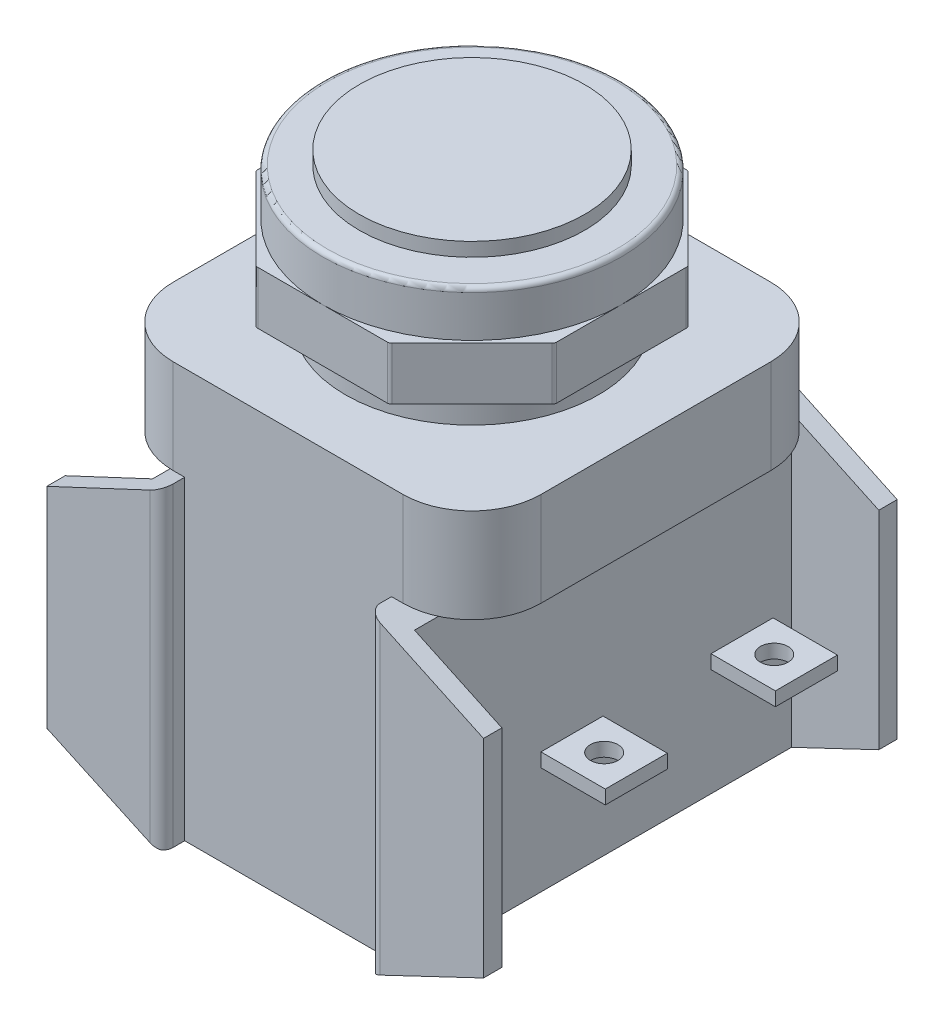
SolidWorks part; units mm, degrees
ref_plane "Front Plane" through (0, 0, 0) normal (0, 0, 1) x (1, 0, 0)
ref_plane "Top Plane" through (0, 0, 0) normal (0, 1, 0) x (1, 0, 0)
ref_plane "Right Plane" through (0, 0, 0) normal (1, 0, 0) x (0, 0, -1)
sketch "Sketch1" plane through (0, 0, 0) normal (0, 1, 0) x (1, 0, 0)
  circle A0 centre (0, 0) radius 12.446
  dimension "D1" = 24.892
extrude "Boss-Extrude1" add sketch "Sketch1" against normal blind 1.524
sketch "Sketch2" plane through (0, -1.524, 0) normal (0, -1, 0) x (1, 0, 0)
  circle A0 centre (0, 0) radius 16.51
  dimension "D1" = 33.02
extrude "Boss-Extrude2" add sketch "Sketch2" along normal blind 5.08
sketch "Sketch3" plane through (0, -6.604, 0) normal (0, -1, 0) x (1, 0, 0)
  line L0 (0, 0) -> (16.51, 0) construction
  line L1 (0, 0) -> (0, -16.51) construction
  line L2 (16.51, 7.366) -> (16.51, -7.366)
  line L3 (-7.366, -16.51) -> (7.366, -16.51)
  line L4 (16.51, -7.366) -> (7.366, -16.51)
  line L5 (-7.366, 16.51) -> (7.366, 16.51)
  line L6 (16.51, 7.366) -> (7.366, 16.51)
  line L7 (-16.51, -7.366) -> (-7.366, -16.51)
  line L8 (-16.51, 7.366) -> (-16.51, -7.366)
  line L9 (-16.51, 7.366) -> (-7.366, 16.51)
  circle A0 centre (0, 0) radius 16.51 construction
  point P16 (0, 16.51)
  dimension "D1" = 7.366
  dimension "D2" = 7.366
extrude "Boss-Extrude3" add sketch "Sketch3" along normal blind 5.842
fillet "Fillet1" radius 0.508 1 edges at (0, -1.524, -16.51)
fillet "Fillet2" radius 0.508 8 edges at (-7.366, -9.525, -16.51) (7.366, -9.525, -16.51) (16.51, -9.525, -7.366) (16.51, -9.525, 7.366) (7.366, -9.525, 16.51) (-7.366, -9.525, 16.51) (-16.51, -9.525, 7.366) (-16.51, -9.525, -7.366)
sketch "Sketch4" plane through (0, -12.446, 0) normal (0, -1, 0) x (1, 0, 0)
  circle A0 centre (0, 0) radius 13.97
  dimension "D1" = 27.94
extrude "Boss-Extrude4" add sketch "Sketch4" along normal blind 4.064
sketch "Sketch5" plane through (0, -16.51, 0) normal (0, -1, 0) x (1, 0, 0)
  line L0 (0, 0) -> (20.32, 0) construction
  line L1 (20.32, 0) -> (20.32, 20.32) construction
  line L2 (12.7, 20.32) -> (-12.7, 20.32)
  line L3 (-20.32, 12.7) -> (-20.32, -12.7)
  line L4 (-12.7, -20.32) -> (12.7, -20.32)
  line L5 (20.32, -12.7) -> (20.32, 12.7)
  arc A0 (-20.32, 12.7) -> (-12.7, 20.32) centre (-12.7, 12.7) cw
  arc A1 (12.7, 20.32) -> (20.32, 12.7) centre (12.7, 12.7) cw
  arc A2 (-20.32, -12.7) -> (-12.7, -20.32) centre (-12.7, -12.7) ccw
  arc A3 (12.7, -20.32) -> (20.32, -12.7) centre (12.7, -12.7) ccw
  point P9 (-20.32, 20.32)
  point P15 (-20.32, -20.32)
  point P18 (20.32, -20.32)
  dimension "D5" = 7.62
  dimension "D6" = 7.62
  dimension "D7" = 7.62
  dimension "D1" = 20.32
  dimension "D2" = 20.32
  dimension "D3" = 40.64
  dimension "D4" = 40.64
extrude "Boss-Extrude5" add sketch "Sketch5" along normal blind 10.414
sketch "Sketch6" plane through (0, -26.924, 0) normal (0, -1, 0) x (1, 0, 0)
  line L0 (0, 0) -> (11.43, 0) construction
  line L1 (11.43, 0) -> (11.43, 20.32) construction
  line L2 (11.43, 20.32) -> (-11.43, 20.32)
  line L3 (12.7, 20.32) -> (-12.7, 20.32) construction
  line L4 (-11.43, 20.32) -> (-11.43, -20.32)
  line L5 (-12.7, -20.32) -> (12.7, -20.32) construction
  line L6 (-11.43, -20.32) -> (11.43, -20.32)
  line L7 (11.43, -20.32) -> (11.43, 20.32)
  dimension "D1" = 11.43
  dimension "D2" = 20.32
  dimension "D3" = 22.86
extrude "Boss-Extrude6" add sketch "Sketch6" along normal blind 34.798
sketch "Sketch7" plane through (0, -61.722, 0) normal (0, -1, 0) x (1, 0, 0)
  line L0 (0, 0) -> (0, 12.7) construction
  line L2 (0, 0) -> (0, -12.7) construction
  circle A0 centre (0, -12.7) radius 2.286
  circle A1 centre (0, 12.7) radius 2.286
  dimension "D3" = 4.572
  dimension "D4" = 4.572
  dimension "D1" = 12.7
  dimension "D2" = 12.7
extrude "Cut-Extrude1" cut sketch "Sketch7" against normal blind 9.398
sketch "Sketch8" plane through (0, 0, -20.32) normal (0, 0, -1) x (-1, 0, 0)
  line L0 (0, 0) -> (0, -26.9952) construction
sketch "Sketch9" plane through (11.43, 0, 0) normal (1, 0, 0) x (0, 0, -1)
  line L0 (0, 0) -> (0, -26.924) construction
  line L1 (20.32, -26.924) -> (-20.32, -26.924) construction
  line L2 (0, -26.924) -> (-22.86, -26.924) construction
  line L3 (22.86, -26.924) -> (-22.86, -26.924)
  line L10 (22.86, -61.722) -> (-22.86, -61.722)
  line L11 (-22.86, -61.722) -> (-22.86, -26.924)
  line L12 (22.86, -61.722) -> (22.86, -26.924)
  dimension "D1" = 22.86
  dimension "D2" = 34.798
extrude "Boss-Extrude7" add sketch "Sketch9" along normal blind 12.7
mirror "Mirror1" about plane through (0, 0, 0) normal (1, 0, 0) of "Boss-Extrude7"
sketch "Sketch10" plane through (24.13, 0, 0) normal (1, 0, 0) x (0, 0, -1)
  line L0 (0, 0) -> (0, -26.924) construction
  line L1 (12.446, 0) -> (-12.446, 0) construction
  line L2 (22.86, -26.924) -> (-22.86, -26.924) construction
  line L3 (0, -26.924) -> (20.828, -26.924) construction
  line L5 (-22.86, -61.722) -> (22.86, -61.722) construction
  line L6 (-20.828, -26.924) -> (20.828, -26.924)
  line L7 (20.828, -26.924) -> (20.828, -61.722)
  line L8 (20.828, -61.722) -> (-20.828, -61.722)
  line L9 (-20.828, -26.924) -> (-20.828, -61.722)
  dimension "D1" = 20.828
extrude "Cut-Extrude2" cut sketch "Sketch10" against normal blind 9.652
mirror "Mirror2" about plane through (0, 0, 0) normal (1, 0, 0) of "Cut-Extrude2"
sketch "Sketch11" plane through (0, 0, -22.86) normal (0, 0, -1) x (-1, 0, 0)
  line L1 (0, -26.9952) -> (-24.13, -26.924) construction
  line L2 (-11.43, -26.924) -> (-24.13, -32.8747)
  line L3 (-24.13, -61.722) -> (-24.13, -26.924) construction
  line L4 (-24.13, -32.8747) -> (-24.13, -26.924)
  line L5 (-24.13, -26.924) -> (-11.43, -26.924)
  line L7 (-24.13, -26.924) -> (-11.43, -26.924) construction
  line L8 (0, -26.9952) -> (0, -44.3942) construction
  line L9 (0, -44.3942) -> (-24.13, -44.323) construction
  line L11 (24.13, -32.8747) -> (24.13, -26.924)
  line L12 (11.43, -26.924) -> (24.13, -32.8747)
  line L13 (24.13, -26.924) -> (11.43, -26.924)
  line L14 (11.3267, -61.9316) -> (24.0616, -56.056)
  line L15 (24.0264, -62.0066) -> (11.3267, -61.9316)
  line L16 (24.0616, -56.056) -> (24.0264, -62.0066)
  line L17 (-24.1976, -55.7711) -> (-24.2327, -61.7217)
  line L18 (-11.5329, -61.7967) -> (-24.1976, -55.7711)
  line L19 (-24.2327, -61.7217) -> (-11.5329, -61.7967)
  dimension "D1" = 5.9507
  dimension "D2" = 17.399
extrude "Cut-Extrude4" cut sketch "Sketch11" against normal through all
sketch "Sketch12" plane through (0, 0, -22.86) normal (0, 0, -1) x (-1, 0, 0)
  line L0 (0, -26.9952) -> (0, -61.722) construction
  line L1 (11.43, -61.722) -> (-11.43, -61.722) construction
  line L2 (0, -61.722) -> (27.3441, -61.722) construction
  line L3 (27.3441, -61.722) -> (27.3441, -56.0754)
  line L4 (27.3441, -56.0754) -> (24.0616, -56.056)
  line L5 (24.0616, -56.056) -> (20.547, -61.722)
  line L6 (20.547, -61.722) -> (27.3441, -61.722)
  line L7 (24.13, -61.722) -> (24.13, -32.8747) construction
  line L8 (24.13, -61.722) -> (24.0281, -61.722) construction
  dimension "D1" = 3.2141
  dimension "D2" = 3.583
  dimension "D3" = 5.6466
extrude "Cut-Extrude5" cut sketch "Sketch12" against normal through all
sketch "Sketch13" plane through (14.478, 0, 0) normal (1, 0, 0) x (0, 0, -1)
  line L0 (0, 0) -> (0, -48.514) construction
  line L1 (0, -48.514) -> (0, -46.99)
  line L2 (0, -46.99) -> (-6.858, -46.99)
  line L3 (-6.858, -46.99) -> (-6.858, -48.514)
  line L4 (-6.858, -48.514) -> (0, -48.514)
  line L5 (0, -46.99) -> (11.938, -46.99) construction
  line L6 (11.938, -46.99) -> (11.938, -48.514)
  line L7 (11.938, -48.514) -> (18.796, -48.514)
  line L8 (18.796, -48.514) -> (18.796, -46.99)
  line L9 (18.796, -46.99) -> (11.938, -46.99)
  dimension "D1" = 48.514
  dimension "D2" = 1.524
  dimension "D3" = 6.858
  dimension "D4" = 11.938
  dimension "D5" = 6.858
  dimension "D6" = 1.524
extrude "Boss-Extrude8" add sketch "Sketch13" along normal blind 7.112
sketch "Sketch14" plane through (-14.478, 0, 0) normal (-1, 0, 0) x (0, 0, 1)
  line L0 (0, 0) -> (0, -44.4149) construction
  line L1 (0, -44.4149) -> (-6.604, -44.4149)
  line L2 (20.828, -28.3522) -> (20.828, -60.4777) construction
  line L3 (20.828, -44.4149) -> (0, -44.4149) construction
  line L4 (-6.604, -44.4149) -> (-6.604, -45.9389)
  line L5 (-6.604, -45.9389) -> (0, -45.9389)
  line L6 (0, -45.9389) -> (0, -44.4149)
  line L7 (0, -44.4149) -> (13.462, -44.4149) construction
  line L8 (13.462, -44.4149) -> (13.462, -45.9389)
  line L9 (13.462, -45.9389) -> (20.066, -45.9389)
  line L10 (20.066, -45.9389) -> (20.066, -44.4149)
  line L11 (20.066, -44.4149) -> (13.462, -44.4149)
  dimension "D1" = 6.604
  dimension "D2" = 1.524
  dimension "D3" = 6.604
  dimension "D4" = 13.462
  dimension "D5" = 6.604
  dimension "D6" = 1.524
extrude "Boss-Extrude9" add sketch "Sketch14" along normal blind 7.112
ref_plane "Plane1" through (0, -38.1, 0) normal (0, 1, 0) x (1, 0, 0)
sketch "Sketch16" plane through (0, -45.9389, 0) normal (0, -1, 0) x (1, 0, 0)
  line L0 (0, 0) -> (-18.034, 0) construction
  line L1 (-21.59, 0) -> (-14.478, 0) construction
  line L2 (-18.034, 0) -> (-18.034, -3.302) construction
  line L3 (-21.59, 16.764) -> (-18.034, 16.764) construction
  line L4 (-18.034, -3.302) -> (-18.034, 16.764) construction
  line L5 (0, 0) -> (18.034, 0) construction
  line L6 (21.59, 0) -> (14.478, 0) construction
  line L7 (18.034, 0) -> (18.034, 3.429) construction
  line L8 (18.034, 0) -> (18.034, -15.367) construction
  line L9 (-14.478, -6.604) -> (-14.478, 0) construction
  line L10 (-21.59, 13.462) -> (-21.59, 20.066) construction
  line L11 (21.59, 3.429) -> (18.034, 3.429) construction
  line L12 (21.59, 6.858) -> (21.59, 0) construction
  line L13 (21.59, -15.367) -> (18.034, -15.367) construction
  line L14 (21.59, -11.938) -> (21.59, -18.796) construction
  circle A0 centre (-18.034, -3.302) radius 1.524
  circle A1 centre (-18.034, 16.764) radius 1.524
  circle A2 centre (18.034, 3.429) radius 1.524
  circle A3 centre (18.034, -15.367) radius 1.524
  dimension "D1" = 3.048
  dimension "D3" = 3.048
  dimension "D4" = 3.048
  dimension "D5" = 3.048
  dimension "D2" = 3.302
extrude "Cut-Extrude7" cut sketch "Sketch16" against normal blind 7.112
sketch "Sketch17" plane through (0, -38.1, 0) normal (0, 1, 0) x (1, 0, 0)
  circle A0 centre (18.034, 15.367) radius 1.524
  circle A1 centre (18.034, -3.429) radius 1.524
  dimension "D1" = 3.048
  dimension "D2" = 3.048
extrude "Cut-Extrude8" cut sketch "Sketch17" against normal blind 12.7
fillet "Fillet3" radius 1.27 4 edges at (-11.43, -44.323, -22.86) (11.43, -44.323, -22.86) (-11.43, -44.323, 22.86) (11.43, -44.323, 22.86)
